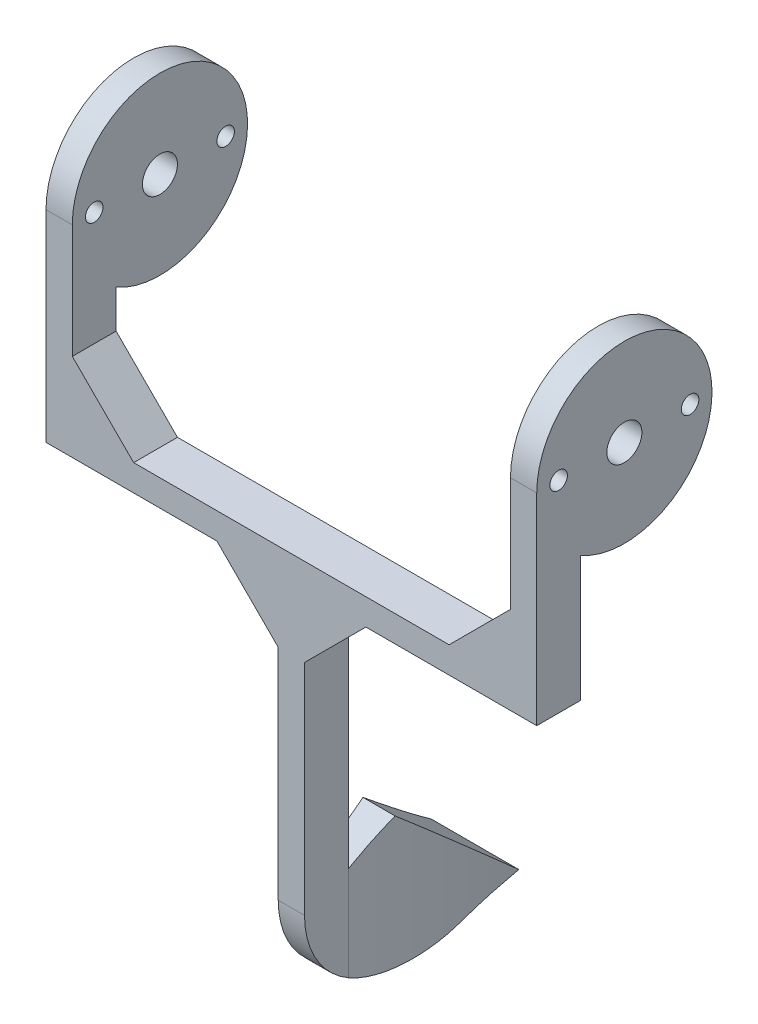
SolidWorks part; units mm, degrees
ref_plane "Front Plane" through (0, 0, 0) normal (0, 0, 1) x (1, 0, 0)
ref_plane "Top Plane" through (0, 0, 0) normal (0, 1, 0) x (1, 0, 0)
ref_plane "Right Plane" through (0, 0, 0) normal (1, 0, 0) x (0, 0, -1)
sketch "Sketch1" plane through (0, 0, 0) normal (0, 0, 1) x (1, 0, 0)
  line L0 (0, 0) -> (-25, 0)
  line L1 (-25, 0) -> (-25, 30)
  line L2 (-25, 30) -> (-28, 30)
  line L3 (0, -3) -> (-28, -3)
  line L4 (-28, -3) -> (-28, 30)
  line L5 (0, 0) -> (0, -3) construction
  line L6 (-28, 30) -> (-28, 120.5928) construction
  line L7 (-25, 30) -> (-25, 120.5928) construction
  line L8 (28, -3) -> (28, 30)
  line L9 (0, -3) -> (28, -3)
  line L10 (25, 30) -> (28, 30)
  line L11 (25, 0) -> (25, 30)
  line L12 (0, 0) -> (25, 0)
  dimension "D1" = 3
  dimension "D2" = 50
  dimension "D3" = 30
extrude "Boss-Extrude1" add sketch "Sketch1" along normal mid plane 20
sketch "Sketch2" plane through (-28, 0, 0) normal (-1, 0, 0) x (0, 0, 1)
  line L0 (10, -3) -> (-10, -3)
  line L1 (-10, -3) -> (-10, 20)
  line L2 (-10, 30) -> (-10, -3) construction
  line L3 (10, 30) -> (10, -3) construction
  line L4 (10, 20) -> (10, -3)
  line L5 (10, 30) -> (-10, 30) construction
  arc A0 (-10, 20) -> (10, 20) centre (0, 20) cw
  circle A1 centre (0, 20) radius 2
  dimension "D1" = 4
extrude "Cut-Extrude1" cut sketch "Sketch2" against normal through all flip side to cut
sketch "Sketch3" plane through (28, 0, 0) normal (1, 0, 0) x (0, 0, -1)
  line L8 (-5, 11.3397) -> (-5, -3)
  line L9 (-10, -3) -> (10, -3) construction
  line L10 (-5, -3) -> (-10, -3)
  line L11 (-10, -3) -> (-10, 20)
  arc A0 (-5, 11.3397) -> (-10, 20) centre (0, 20) ccw
  arc A1 (10, 20) -> (-10, 20) centre (0, 20) ccw construction
  dimension "D1" = 5
extrude "Cut-Extrude2" cut sketch "Sketch3" against normal through all flip side to cut
sketch "Sketch4" plane through (0, 0, 0) normal (1, 0, 0) x (0, 0, -1)
  line L0 (-5, -3) -> (-5, 11.3397) construction
  line L1 (-10, -3) -> (-5, -3)
  line L2 (-10, -3) -> (-10, -35)
  line L4 (-5, -3) -> (-5, -32.8868)
  line L5 (0, -45) -> (0, -30)
  line L6 (0, -30) -> (-5, -32.8868)
  arc A0 (-10, -35) -> (0, -45) centre (0, -35) ccw
  circle A1 centre (0, 20) radius 2 construction
  dimension "D1" = 60
  dimension "D4" = 65
  dimension "D2" = 5
  dimension "D3" = 15
extrude "Boss-Extrude2" add sketch "Sketch4" along normal mid plane 3
sketch "Sketch5" plane through (0, 0, 0) normal (1, 0, 0) x (0, 0, -1)
  line L0 (0, -30) -> (-5, -32.8868) construction
  line L1 (0, -30) -> (-5, -32.8868)
  line L2 (-5, -32.8868) -> (-10, -32.8868)
  line L3 (-10, -3) -> (-10, -35) construction
  line L4 (-10, -32.8868) -> (-10, -35)
  line L5 (6.1023, -42.9222) -> (10.95, -39.1882)
  line L6 (10.95, -39.1882) -> (0, -30)
  arc A0 (-10, -35) -> (0, -45) centre (0, -35) ccw construction
  arc A2 (-10, -35) -> (6.1023, -42.9222) centre (0, -35) ccw
  dimension "D1" = 50
  dimension "D2" = 160
extrude "Boss-Extrude3" add sketch "Sketch5" along normal mid plane 10
sketch "Sketch6" plane through (0, -3, 0) normal (0, -1, 0) x (1, 0, 0)
  line L0 (-1.5, 10) -> (1.5, 10)
  line L1 (5, 10) -> (-5, 10) construction
  line L2 (1.5, 10) -> (1.5, 5)
  line L3 (1.5, 5) -> (28, 5) construction
  line L4 (5, -10.95) -> (-5, -10.95)
  line L5 (5, -10.95) -> (-5, -10.95) construction
  line L6 (0, 10) -> (0, -10.95) construction
  line L7 (-1.5, 10) -> (-1.5, 5)
  arc A0 (1.5, 5) -> (5, -10.95) centre (39.5933, 5) ccw
  arc A1 (-1.5, 5) -> (-5, -10.95) centre (-39.5933, 5) cw
extrude "Cut-Extrude3" cut sketch "Sketch6" along normal through all flip side to cut
sketch "Sketch7" plane through (28, 0, 0) normal (1, 0, 0) x (0, 0, -1)
  line L0 (-7.5, 20) -> (7.5, 20) construction
  circle A0 centre (-7.5, 20) radius 1
  circle A1 centre (7.5, 20) radius 1
  circle A2 centre (0, 20) radius 2 construction
  point P4 (0, 20)
  dimension "D1" = 15
  dimension "D2" = 2
extrude "Cut-Extrude4" cut sketch "Sketch7" against normal through all
sketch "Sketch8" plane through (0, 0, 10) normal (0, 0, 1) x (1, 0, 0)
  line L0 (-25, 0) -> (-25, 7)
  line L1 (-25, 0) -> (-25, 20) construction
  line L2 (-25, 7) -> (-18, 0)
  line L3 (25, 0) -> (-25, 0) construction
  line L4 (-18, 0) -> (-25, 0)
  line L5 (-8.5, -3) -> (-1.5, -3)
  line L6 (-28, -3) -> (-1.5, -3) construction
  line L7 (-8.5, -3) -> (-1.5, -10)
  line L8 (-1.5, -3) -> (-1.5, -35) construction
  line L9 (-1.5, -10) -> (-1.5, -3)
  line L10 (0, 0) -> (0, -45) construction
  line L11 (-1.8296, -45) -> (1.8296, -45) construction
  line L12 (1.5, -10) -> (1.5, -3)
  line L13 (8.5, -3) -> (1.5, -10)
  line L14 (8.5, -3) -> (1.5, -3)
  line L15 (18, 0) -> (25, 0)
  line L16 (25, 7) -> (18, 0)
  line L17 (25, 0) -> (25, 7)
  dimension "D1" = 45
  dimension "D2" = 45
  dimension "D3" = 7
extrude "Boss-Extrude4" add sketch "Sketch8" against normal up to surface (5 mm away) up to face at (0, -2.7012, 5)
